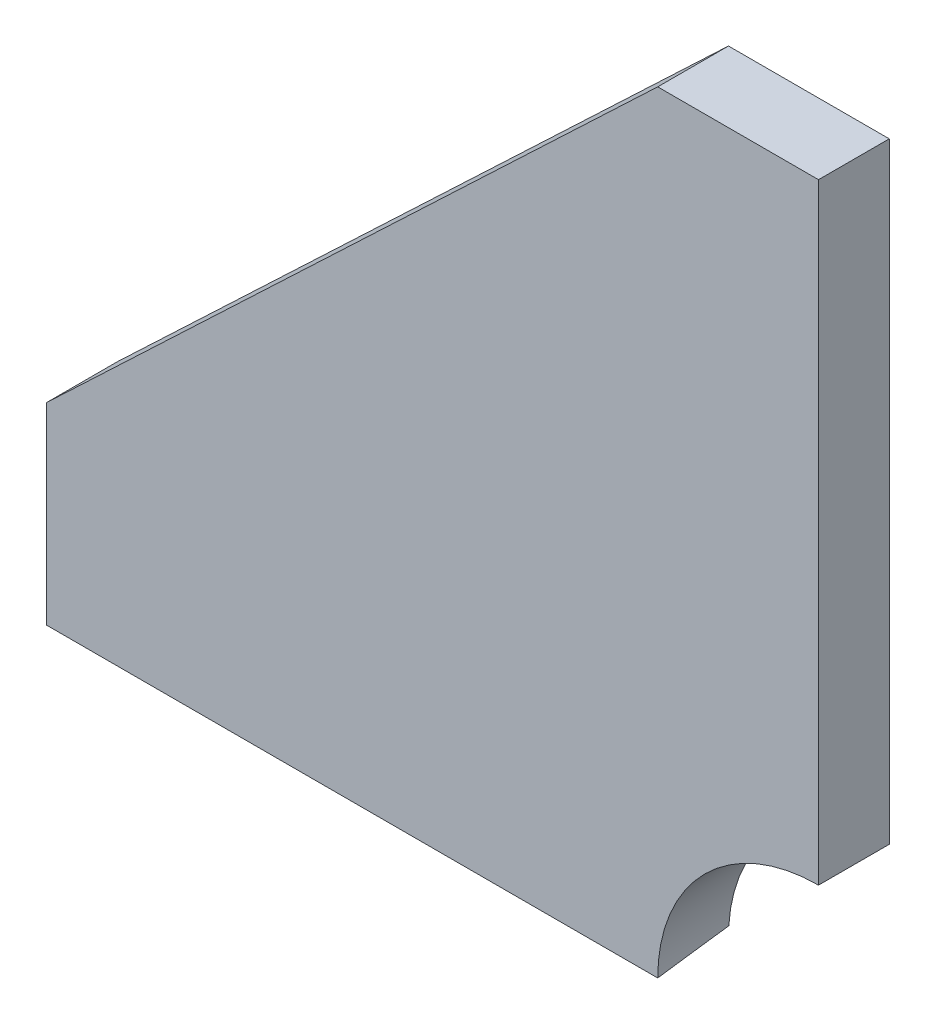
SolidWorks part; units mm, degrees
material "1.0116 (S235J2G3)"
ref_plane "Front Plane" through (0, 0, 0) normal (0, 0, 1) x (1, 0, 0)
ref_plane "Top Plane" through (0, 0, 0) normal (0, 1, 0) x (1, 0, 0)
ref_plane "Right Plane" through (0, 0, 0) normal (1, 0, 0) x (0, 0, -1)
sketch "Sketch1" plane through (0, 0, 0) normal (0, 0, 1) x (1, 0, 0)
  line L0 (0, 0) -> (25, 0)
  line L1 (25, 0) -> (25, -120)
  line L2 (0, 0) -> (-95, -90)
  line L3 (-95, -90) -> (-95, -120)
  line L4 (-95, -120) -> (25, -120)
  circle A0 centre (25, -120) radius 25
  dimension "D5" = 50
  dimension "D1" = 25
  dimension "D2" = 120
  dimension "D3" = 120
  dimension "D4" = 30
extrude "Boss-Extrude1" add sketch "Sketch1" along normal blind 11 contours A0 L1 L0 L2 L3 L4
sketch "Sketch2" plane through (-95, 0, 0) normal (-1, 0, 0) x (0, 0, 1)
  line L0 (0, -120) -> (0, -118.4541)
  line L1 (0, -90) -> (0, -120) construction
  line L2 (0, -118.4541) -> (11, -120)
  line L3 (11, -120) -> (0, -120)
  dimension "D1" = 8
extrude "Cut-Extrude1" cut sketch "Sketch2" against normal blind 114
